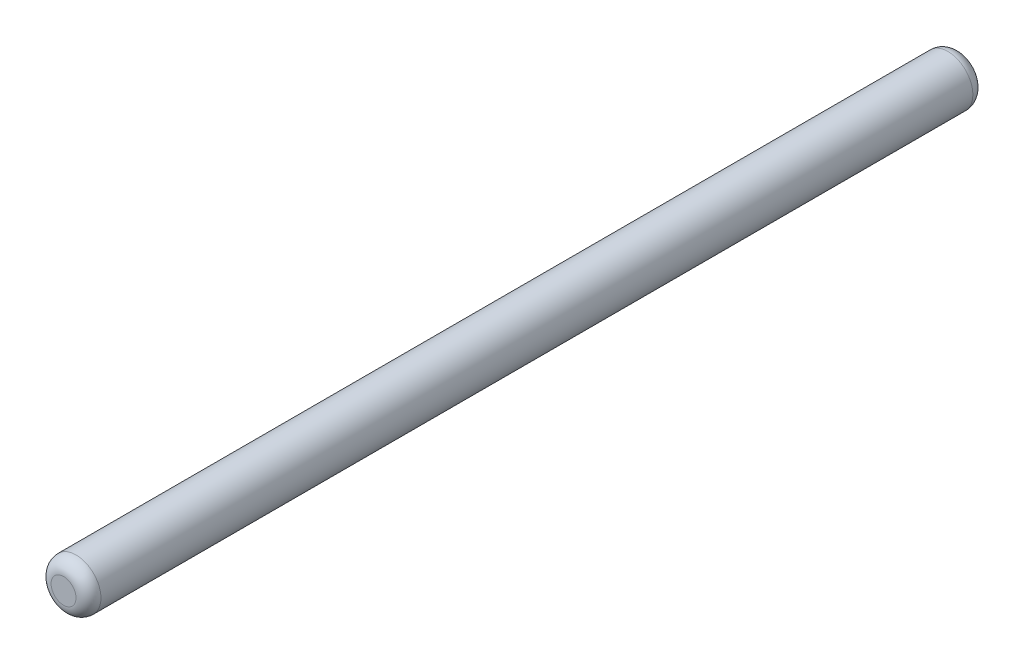
SolidWorks part; units mm, degrees
ref_plane "Front Plane" through (0, 0, 0) normal (0, 0, 1) x (1, 0, 0)
ref_plane "Top Plane" through (0, 0, 0) normal (0, 1, 0) x (1, 0, 0)
ref_plane "Right Plane" through (0, 0, 0) normal (1, 0, 0) x (0, 0, -1)
sketch "Sketch1" plane through (0, 0, 0) normal (0, 0, 1) x (1, 0, 0)
  circle A0 centre (0, 0) radius 4
  dimension "D1" = 8
extrude "Boss-Extrude1" add sketch "Sketch1" along normal blind 144
fillet "Fillet1" radius 2 2 edges at (4, 0, 144) (4, 0, 0)
